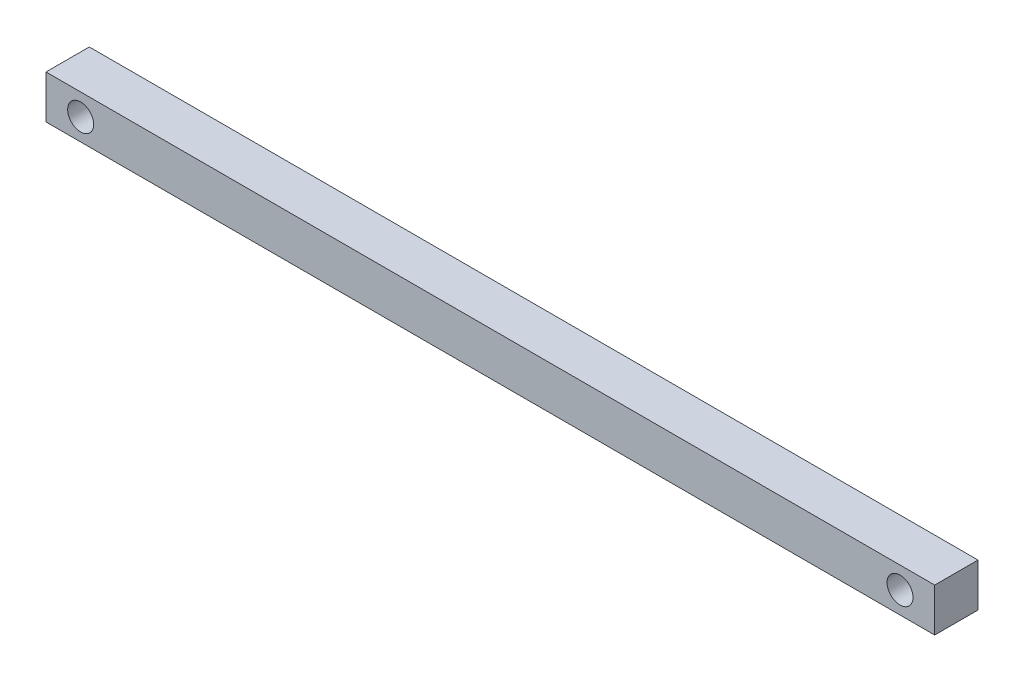
SolidWorks part; units mm, degrees
ref_plane "Front Plane" through (0, 0, 0) normal (0, 0, 1) x (1, 0, 0)
ref_plane "Top Plane" through (0, 0, 0) normal (0, 1, 0) x (1, 0, 0)
ref_plane "Right Plane" through (0, 0, 0) normal (1, 0, 0) x (0, 0, -1)
sketch "Sketch1" plane through (0, 0, 0) normal (0, 0, 1) x (1, 0, 0)
  line L0 (-718.9217, 0) -> (748.6474, 0) construction
  line L1 (0, 373.2227) -> (0, -433.7751) construction
  line L3 (-256.5, 12.5) -> (256.5, 12.5)
  line L4 (-256.5, 12.5) -> (-256.5, -12.5)
  line L5 (-256.5, -12.5) -> (256.5, -12.5)
  line L6 (256.5, 12.5) -> (256.5, -12.5)
  circle A0 centre (-236.5, 0) radius 7.5
  circle A1 centre (236.5, 0) radius 7.5
  point P5 (0, 0)
  dimension "D3" = 15
  dimension "D4" = 15
  dimension "D1" = 513
  dimension "D2" = 25
  dimension "D5" = 236.5
  dimension "D6" = 236.5
extrude "Boss-Extrude1" add sketch "Sketch1" along normal blind 25
